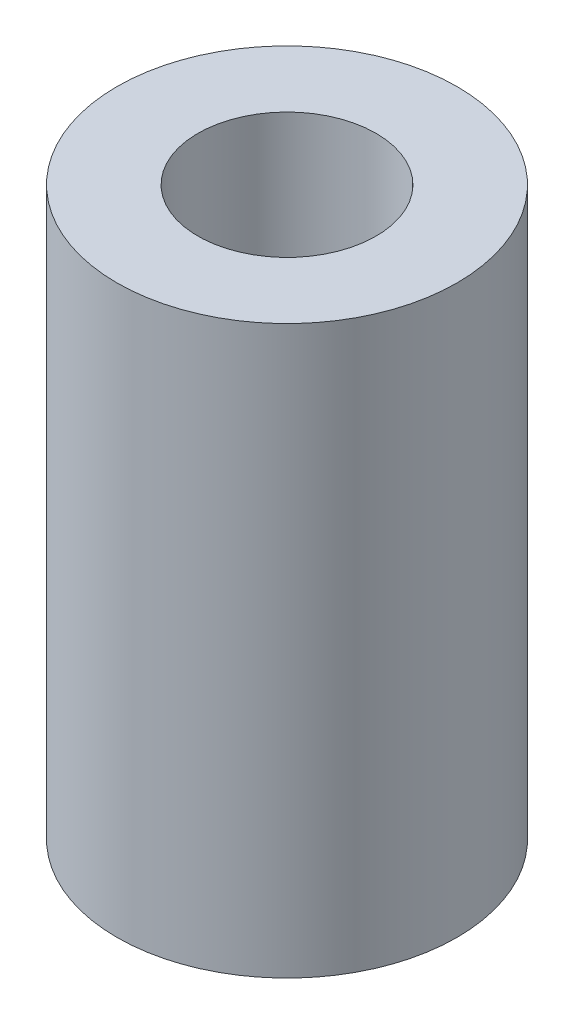
SolidWorks part; units mm, degrees
ref_plane "前视基准面" through (0, 0, 0) normal (0, 0, 1) x (1, 0, 0)
ref_plane "上视基准面" through (0, 0, 0) normal (0, 1, 0) x (1, 0, 0)
ref_plane "右视基准面" through (0, 0, 0) normal (1, 0, 0) x (0, 0, -1)
sketch "草图1" plane through (0, 0, 0) normal (0, 1, 0) x (1, 0, 0)
  circle A0 centre (0, 0) radius 1.65
  circle A1 centre (0, 0) radius 3.15
  dimension "D1" = 3.3
  dimension "D2" = 1.5
extrude "凸台-拉伸1" add sketch "草图1" along normal blind 10.5
